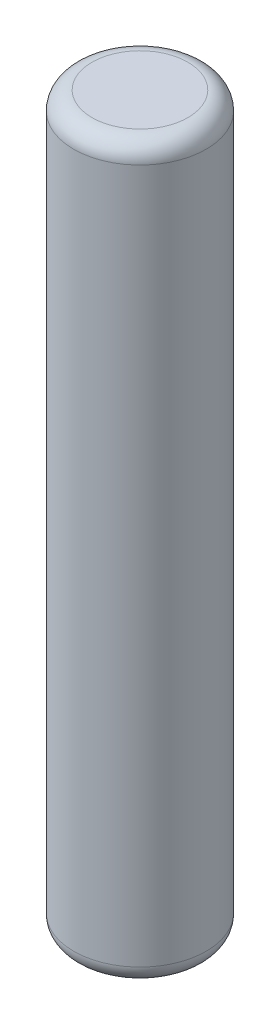
SolidWorks part; units mm, degrees
material "Pin"
ref_plane "Plan de face" through (0, 0, 0) normal (0, 0, 1) x (1, 0, 0)
ref_plane "Plan de dessus" through (0, 0, 0) normal (0, 1, 0) x (1, 0, 0)
ref_plane "Plan de droite" through (0, 0, 0) normal (1, 0, 0) x (0, 0, -1)
sketch "Esquisse1" plane through (0, 0, 0) normal (0, 1, 0) x (1, 0, 0)
  circle A0 centre (0, 0) radius 3.625
  dimension "D1" = 7.25
extrude "Boss.-Extru.1" add sketch "Esquisse1" along normal blind 40
fillet "Congé1" radius 1 1 edges at (0, 40, 3.625)
fillet "Congé2" radius 1 1 edges at (0, 0, 3.625)
